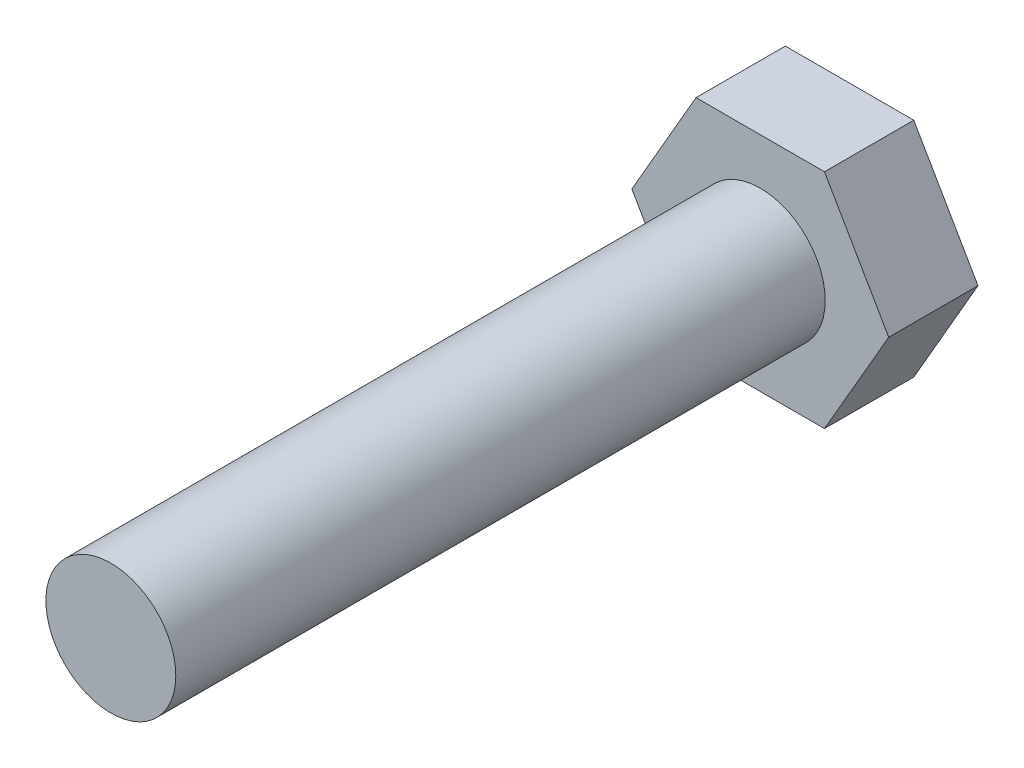
SolidWorks part; units mm, degrees
ref_plane "正面" through (0, 0, 0) normal (0, 0, 1) x (1, 0, 0)
ref_plane "平面" through (0, 0, 0) normal (0, 1, 0) x (1, 0, 0)
ref_plane "右側面" through (0, 0, 0) normal (1, 0, 0) x (0, 0, -1)
sketch "ｽｹｯﾁ1" plane through (0, 0, 0) normal (0, 0, 1) x (1, 0, 0)
  line L1 (3.9548, 0) -> (1.9774, 3.425)
  line L2 (1.9774, 3.425) -> (-1.9774, 3.425)
  line L3 (-1.9774, 3.425) -> (-3.9548, 0)
  line L4 (-3.9548, 0) -> (-1.9774, -3.425)
  line L5 (-1.9774, -3.425) -> (1.9774, -3.425)
  line L6 (1.9774, -3.425) -> (3.9548, 0)
  circle A0 centre (0, 0) radius 3.425 construction
  dimension "D1" = 6.85
extrude "ﾎﾞｽ - 押し出し1" add sketch "ｽｹｯﾁ1" along normal blind 2.75
sketch "ｽｹｯﾁ2" plane through (0, 0, 2.75) normal (0, 0, 1) x (1, 0, 0)
  circle A0 centre (0, 0) radius 2
  dimension "D1" = 4
extrude "ﾎﾞｽ - 押し出し2" add sketch "ｽｹｯﾁ2" along normal blind 20
